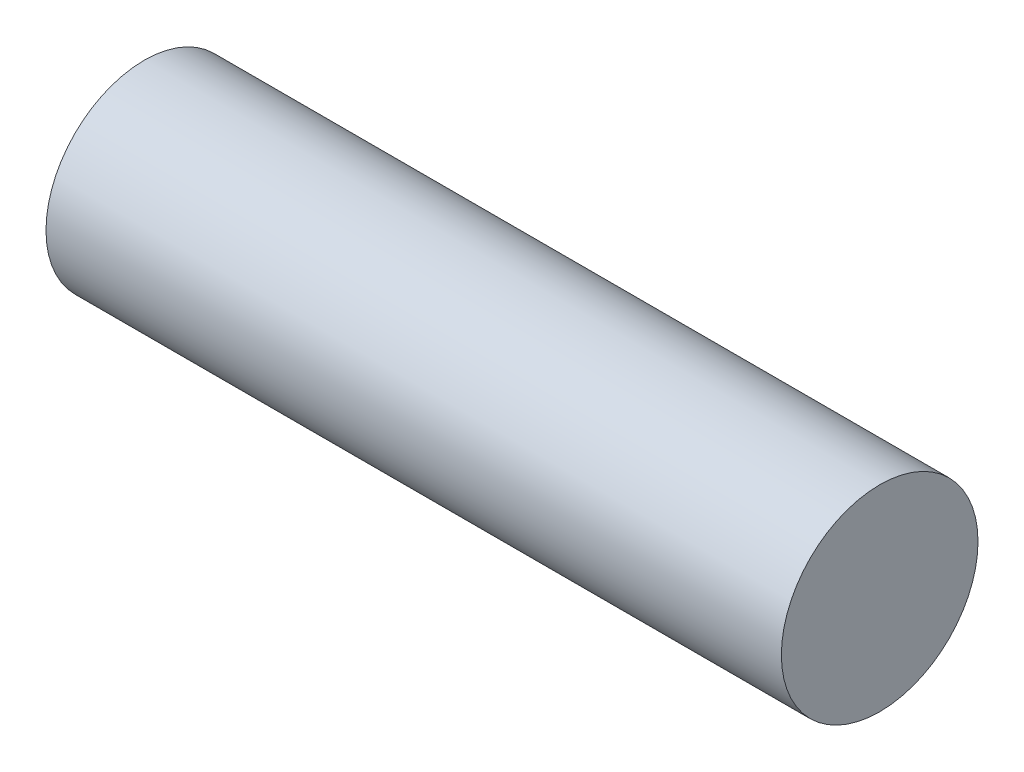
SolidWorks part; units mm, degrees
ref_plane "Front Plane" through (0, 0, 0) normal (0, 0, 1) x (1, 0, 0)
ref_plane "Top Plane" through (0, 0, 0) normal (0, 1, 0) x (1, 0, 0)
ref_plane "Right Plane" through (0, 0, 0) normal (1, 0, 0) x (0, 0, -1)
sketch "Sketch1" plane through (0, 0, 0) normal (1, 0, 0) x (0, 0, -1)
  circle A0 centre (0, 0) radius 4
  dimension "D1" = 8
extrude "Boss-Extrude1" add sketch "Sketch1" along normal blind 29.92
